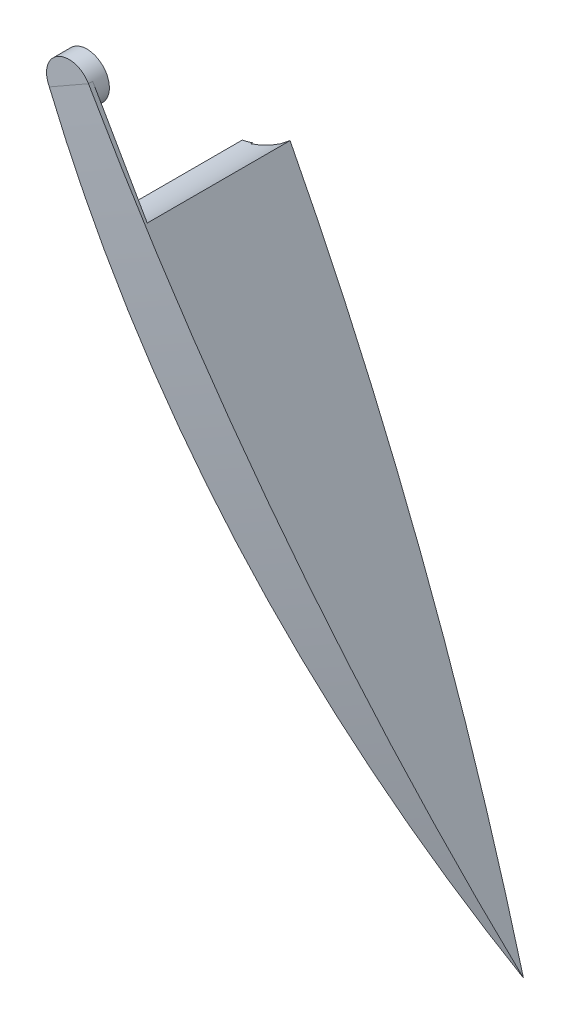
SolidWorks part; units mm, degrees
ref_plane "Plan de face" through (0, 0, 0) normal (0, 0, 1) x (1, 0, 0)
ref_plane "Plan de dessus" through (0, 0, 0) normal (0, 1, 0) x (1, 0, 0)
ref_plane "Plan de droite" through (0, 0, 0) normal (1, 0, 0) x (0, 0, -1)
sketch "Esquisse1" plane through (0, 0, 0) normal (0, 0, 1) x (1, 0, 0)
  line L0 (-5.7517, -9.8772) -> (-6.8338, -9.7825) construction
  line L1 (-6.8338, -9.7825) -> (-6.9494, -9.1264) construction
  line L2 (-6.9494, -9.1264) -> (-5.9535, -8.662) construction
  line L3 (-6.0657, -8.3442) -> (-7.1383, -8.6316) construction
  line L4 (-7.1383, -8.6316) -> (-7.4714, -8.0546) construction
  line L5 (-7.4714, -8.0546) -> (-6.6788, -7.262) construction
  line L6 (-6.8912, -7.0053) -> (-7.818, -7.6542) construction
  line L7 (-7.818, -7.6542) -> (-8.3284, -7.226) construction
  line L8 (-8.3284, -7.226) -> (-7.8476, -6.1949) construction
  line L9 (-8.1333, -6.0289) -> (-8.7911, -6.9683) construction
  line L10 (-8.7911, -6.9683) -> (-9.4172, -6.7405) construction
  line L11 (-9.4172, -6.7405) -> (-9.3172, -5.5977) construction
  line L12 (-9.6413, -5.5414) -> (-9.9401, -6.6566) construction
  line L13 (-9.9401, -6.6566) -> (-10.6064, -6.6566) construction
  line L14 (-10.6064, -6.6566) -> (-10.9035, -5.5477) construction
  line L15 (-11.227, -5.6073) -> (-11.1264, -6.7566) construction
  line L16 (-11.1264, -6.7566) -> (-11.7525, -6.9845) construction
  line L17 (-11.7525, -6.9845) -> (-12.4065, -6.0504) construction
  line L18 (-12.6906, -6.2193) -> (-12.207, -7.2564) construction
  line L19 (-12.207, -7.2564) -> (-12.7173, -7.6846) construction
  line L20 (-12.7173, -7.6846) -> (-13.6389, -7.0393) construction
  line L21 (-13.8487, -7.2983) -> (-13.0514, -8.0955) construction
  line L22 (-13.0514, -8.0955) -> (-13.3846, -8.6725) construction
  line L23 (-13.3846, -8.6725) -> (-14.4509, -8.3868) construction
  line L24 (-14.5599, -8.7057) -> (-13.558, -9.1729) construction
  line L25 (-13.558, -9.1729) -> (-13.6737, -9.8291) construction
  line L26 (-13.6737, -9.8291) -> (-14.7493, -9.9232) construction
  line L27 (-14.7422, -10.2644) -> (-13.6655, -10.3586) construction
  line L28 (-13.6655, -10.3586) -> (-13.5498, -11.0147) construction
  line L29 (-13.5498, -11.0147) -> (-14.5063, -11.4608) construction
  line L30 (-14.3817, -11.783) -> (-13.3609, -11.5095) construction
  line L31 (-13.3609, -11.5095) -> (-13.0278, -12.0865) construction
  line L32 (-13.0278, -12.0865) -> (-13.7588, -12.8175) construction
  line L33 (-13.5298, -13.0811) -> (-12.6812, -12.4869) construction
  line L34 (-12.6812, -12.4869) -> (-12.1708, -12.9151) construction
  line L35 (-12.1708, -12.9151) -> (-12.6007, -13.8372) construction
  line L36 (-12.2937, -14.0091) -> (-11.7081, -13.1728) construction
  line L37 (-11.7081, -13.1728) -> (-11.082, -13.4007) construction
  line L38 (-11.082, -13.4007) -> (-11.1699, -14.405) construction
  line L39 (-10.8214, -14.4636) -> (-10.5591, -13.4845) construction
  line L40 (-10.5591, -13.4845) -> (-9.8929, -13.4845) construction
  line L41 (-9.8929, -13.4845) -> (-9.6322, -14.4574) construction
  line L42 (-9.2844, -14.3952) -> (-9.3728, -13.3845) construction
  line L43 (-9.3728, -13.3845) -> (-8.7467, -13.1566) construction
  line L44 (-8.7467, -13.1566) -> (-8.1648, -13.9877) construction
  line L45 (-7.8596, -13.8126) -> (-8.2922, -12.8848) construction
  line L46 (-8.2922, -12.8848) -> (-7.7819, -12.4565) construction
  line L47 (-7.7819, -12.4565) -> (-6.9385, -13.047) construction
  line L48 (-6.7123, -12.7811) -> (-7.4478, -12.0456) construction
  line L49 (-7.4478, -12.0456) -> (-7.1146, -11.4686) construction
  line L50 (-7.1146, -11.4686) -> (-6.1002, -11.7404) construction
  line L51 (-5.9789, -11.4169) -> (-6.9412, -10.9682) construction
  line L52 (-6.9412, -10.9682) -> (-6.8255, -10.3121) construction
  line L53 (-6.8255, -10.3121) -> (-5.7553, -10.2184) construction
  line L54 (-5.7517, -9.8772) -> (-6.8338, -9.7825)
  line L55 (-6.8338, -9.7825) -> (-6.9494, -9.1264)
  line L56 (-6.9494, -9.1264) -> (-5.9535, -8.662)
  line L57 (-6.0657, -8.3442) -> (-7.1383, -8.6316)
  line L58 (-7.1383, -8.6316) -> (-7.4714, -8.0546)
  line L59 (-7.4714, -8.0546) -> (-6.6788, -7.262)
  line L60 (-6.8912, -7.0053) -> (-7.818, -7.6542)
  line L61 (-7.818, -7.6542) -> (-8.3284, -7.226)
  line L62 (-8.3284, -7.226) -> (-7.8476, -6.1949)
  line L63 (-8.1333, -6.0289) -> (-8.7911, -6.9683)
  line L64 (-8.7911, -6.9683) -> (-9.4172, -6.7405)
  line L65 (-9.4172, -6.7405) -> (-9.3172, -5.5977)
  line L66 (-9.6413, -5.5414) -> (-9.9401, -6.6566)
  line L67 (-9.9401, -6.6566) -> (-10.6064, -6.6566)
  line L68 (-10.6064, -6.6566) -> (-10.9035, -5.5477)
  line L69 (-11.227, -5.6073) -> (-11.1264, -6.7566)
  line L70 (-11.1264, -6.7566) -> (-11.7525, -6.9845)
  line L71 (-11.7525, -6.9845) -> (-12.4065, -6.0504)
  line L72 (-12.6906, -6.2193) -> (-12.207, -7.2564)
  line L73 (-12.207, -7.2564) -> (-12.7173, -7.6846)
  line L74 (-12.7173, -7.6846) -> (-13.6389, -7.0393)
  line L75 (-13.8487, -7.2983) -> (-13.0514, -8.0955)
  line L76 (-13.0514, -8.0955) -> (-13.3846, -8.6725)
  line L77 (-13.3846, -8.6725) -> (-14.4509, -8.3868)
  line L78 (-14.5599, -8.7057) -> (-13.558, -9.1729)
  line L79 (-13.558, -9.1729) -> (-13.6737, -9.8291)
  line L80 (-13.6737, -9.8291) -> (-14.7493, -9.9232)
  line L81 (-14.7422, -10.2644) -> (-13.6655, -10.3586)
  line L82 (-13.6655, -10.3586) -> (-13.5498, -11.0147)
  line L83 (-13.5498, -11.0147) -> (-14.5063, -11.4608)
  line L84 (-14.3817, -11.783) -> (-13.3609, -11.5095)
  line L85 (-13.3609, -11.5095) -> (-13.0278, -12.0865)
  line L86 (-13.0278, -12.0865) -> (-13.7588, -12.8175)
  line L87 (-13.5298, -13.0811) -> (-12.6812, -12.4869)
  line L88 (-12.6812, -12.4869) -> (-12.1708, -12.9151)
  line L89 (-12.1708, -12.9151) -> (-12.6007, -13.8372)
  line L90 (-12.2937, -14.0091) -> (-11.7081, -13.1728)
  line L91 (-11.7081, -13.1728) -> (-11.082, -13.4007)
  line L92 (-11.082, -13.4007) -> (-11.1699, -14.405)
  line L93 (-10.8214, -14.4636) -> (-10.5591, -13.4845)
  line L94 (-10.5591, -13.4845) -> (-9.8929, -13.4845)
  line L95 (-9.8929, -13.4845) -> (-9.6322, -14.4574)
  line L96 (-9.2844, -14.3952) -> (-9.3728, -13.3845)
  line L97 (-9.3728, -13.3845) -> (-8.7467, -13.1566)
  line L98 (-8.7467, -13.1566) -> (-8.1648, -13.9877)
  line L99 (-7.8596, -13.8126) -> (-8.2922, -12.8848)
  line L100 (-8.2922, -12.8848) -> (-7.7819, -12.4565)
  line L101 (-7.7819, -12.4565) -> (-6.9385, -13.047)
  line L102 (-6.7123, -12.7811) -> (-7.4478, -12.0456)
  line L103 (-7.4478, -12.0456) -> (-7.1146, -11.4686)
  line L104 (-7.1146, -11.4686) -> (-6.1002, -11.7404)
  line L105 (-5.9789, -11.4169) -> (-6.9412, -10.9682)
  line L106 (-6.9412, -10.9682) -> (-6.8255, -10.3121)
  line L107 (-6.8255, -10.3121) -> (-5.7553, -10.2184)
  circle A0 centre (-10.25, -10) radius 8 construction
  arc A1 (-5.9535, -8.662) -> (-6.0657, -8.3442) centre (-10.25, -10) ccw construction
  arc A2 (-6.6788, -7.262) -> (-6.8912, -7.0053) centre (-10.25, -10) ccw construction
  arc A3 (-7.8476, -6.1949) -> (-8.1333, -6.0289) centre (-10.25, -10) ccw construction
  arc A4 (-9.3172, -5.5977) -> (-9.6413, -5.5414) centre (-10.25, -10) ccw construction
  arc A5 (-10.9035, -5.5477) -> (-11.227, -5.6073) centre (-10.25, -10) ccw construction
  arc A6 (-12.4065, -6.0504) -> (-12.6906, -6.2193) centre (-10.25, -10) ccw construction
  arc A7 (-13.6389, -7.0393) -> (-13.8487, -7.2983) centre (-10.25, -10) ccw construction
  arc A8 (-14.4509, -8.3868) -> (-14.5599, -8.7057) centre (-10.25, -10) ccw construction
  arc A9 (-14.7493, -9.9232) -> (-14.7422, -10.2644) centre (-10.25, -10) ccw construction
  arc A10 (-14.5063, -11.4608) -> (-14.3817, -11.783) centre (-10.25, -10) ccw construction
  arc A11 (-13.7588, -12.8175) -> (-13.5298, -13.0811) centre (-10.25, -10) ccw construction
  arc A12 (-12.6007, -13.8372) -> (-12.2937, -14.0091) centre (-10.25, -10) ccw construction
  arc A13 (-11.1699, -14.405) -> (-10.8214, -14.4636) centre (-10.25, -10) ccw construction
  arc A14 (-9.6322, -14.4574) -> (-9.2844, -14.3952) centre (-10.25, -10) ccw construction
  arc A15 (-8.1648, -13.9877) -> (-7.8596, -13.8126) centre (-10.25, -10) ccw construction
  arc A16 (-6.9385, -13.047) -> (-6.7123, -12.7811) centre (-10.25, -10) ccw construction
  arc A17 (-6.1002, -11.7404) -> (-5.9789, -11.4169) centre (-10.25, -10) ccw construction
  arc A18 (-5.7553, -10.2184) -> (-5.7517, -9.8772) centre (-10.25, -10) ccw construction
  circle A19 centre (-10.25, -10) radius 8
  arc A20 (-5.9535, -8.662) -> (-6.0657, -8.3442) centre (-10.25, -10) ccw
  arc A21 (-6.6788, -7.262) -> (-6.8912, -7.0053) centre (-10.25, -10) ccw
  arc A22 (-7.8476, -6.1949) -> (-8.1333, -6.0289) centre (-10.25, -10) ccw
  arc A23 (-9.3172, -5.5977) -> (-9.6413, -5.5414) centre (-10.25, -10) ccw
  arc A24 (-10.9035, -5.5477) -> (-11.227, -5.6073) centre (-10.25, -10) ccw
  arc A25 (-12.4065, -6.0504) -> (-12.6906, -6.2193) centre (-10.25, -10) ccw
  arc A26 (-13.6389, -7.0393) -> (-13.8487, -7.2983) centre (-10.25, -10) ccw
  arc A27 (-14.4509, -8.3868) -> (-14.5599, -8.7057) centre (-10.25, -10) ccw
  arc A28 (-14.7493, -9.9232) -> (-14.7422, -10.2644) centre (-10.25, -10) ccw
  arc A29 (-14.5063, -11.4608) -> (-14.3817, -11.783) centre (-10.25, -10) ccw
  arc A30 (-13.7588, -12.8175) -> (-13.5298, -13.0811) centre (-10.25, -10) ccw
  arc A31 (-12.6007, -13.8372) -> (-12.2937, -14.0091) centre (-10.25, -10) ccw
  arc A32 (-11.1699, -14.405) -> (-10.8214, -14.4636) centre (-10.25, -10) ccw
  arc A33 (-9.6322, -14.4574) -> (-9.2844, -14.3952) centre (-10.25, -10) ccw
  arc A34 (-8.1648, -13.9877) -> (-7.8596, -13.8126) centre (-10.25, -10) ccw
  arc A35 (-6.9385, -13.047) -> (-6.7123, -12.7811) centre (-10.25, -10) ccw
  arc A36 (-6.1002, -11.7404) -> (-5.9789, -11.4169) centre (-10.25, -10) ccw
  arc A37 (-5.7553, -10.2184) -> (-5.7517, -9.8772) centre (-10.25, -10) ccw
extrude "Boss.-Extru.1" add sketch "Esquisse1" against normal blind 4.9
sketch "Esquisse2" plane through (0, 0, 0) normal (0, 0, 1) x (1, 0, 0)
  line L1 (-17.6401, -13.0637) -> (-17.6393, -13.0657)
  line L2 (-17.6401, -13.0637) -> (-17.6393, -13.0657)
  line L3 (-3.3034, -6.0321) -> (125.1907, -230.9881)
  circle A0 centre (-10.25, -10) radius 8 construction
  arc A1 (-3.3034, -6.0321) -> (-17.6393, -13.0657) centre (-10.25, -10) ccw
  arc A2 (-17.6393, -13.0657) -> (125.1907, -230.9881) centre (629.9765, 255.6247) ccw
extrude "Boss.-Extru.2" add sketch "Esquisse2" along normal blind 1.5 contours L1 A2 L3 A1
sketch "Esquisse3" plane through (0, 0, 0) normal (0, 0, -1) x (-1, 0, 0)
  line L1 (3.3034, -6.0321) -> (-125.1907, -230.9881)
  line L2 (-16.1353, -40.0636) -> (-125.1907, -230.9881)
  arc A0 (-16.1353, -40.0636) -> (1.5164, -49.0349) centre (10.25, -10) ccw
  arc A2 (3.3034, -6.0321) -> (17.6393, -13.0657) centre (10.25, -10) ccw
  arc A3 (-125.1907, -230.9881) -> (17.6393, -13.0657) centre (-629.9765, 255.6247) ccw
  arc A5 (-125.1907, -230.9881) -> (1.5164, -49.0349) centre (-629.9765, 255.6247) ccw
  point P5 (-24.4832, 9.8395)
  point P7 (47.1963, -25.3287)
  dimension "D1" = 0
extrude "Boss.-Extru.3" add sketch "Esquisse3" along normal up to vertex (51.5 mm away)
sketch "Esquisse4" plane through (-5.0886, -2.9066, 0) normal (0.8683, 0.496, 0) x (0, 0, -1)
  line L0 (-1.5, -262.6668) -> (51.5, -262.6668) construction
  line L1 (-1.5, -262.6668) -> (51.5, -262.6668)
  line L2 (-1.5, -3.5994) -> (-1.5, -262.6668) construction
  line L4 (-1.5, -3.5994) -> (-1.5, -262.6668)
  line L5 (25, -262.6668) -> (25, -234.7779) construction
  line L6 (51.5, -42.7913) -> (51.5, -262.6668) construction
  line L7 (51.5, -42.7913) -> (51.5, -262.6668)
  arc A0 (-1.5, -3.5994) -> (25, -262.6668) centre (1278.088, -3.5994) ccw
  arc A1 (51.5, -3.5994) -> (25, -262.6668) centre (-1228.088, -3.5994) cw
  line M5 (-1.5, -3.5994) -> (-1.5, -262.6668)
  line M6 (-1.5, -262.6668) -> (51.5, -262.6668)
  line M7 (51.5, -262.6668) -> (51.5, -42.7913)
  line M8 (51.5, -42.7913) -> (0, -42.7913)
extrude "Enlèv. mat.-Extru.1" cut sketch "Esquisse4" against normal blind 25 contours A0 M5 M6 | A1 L1 M8 M7
